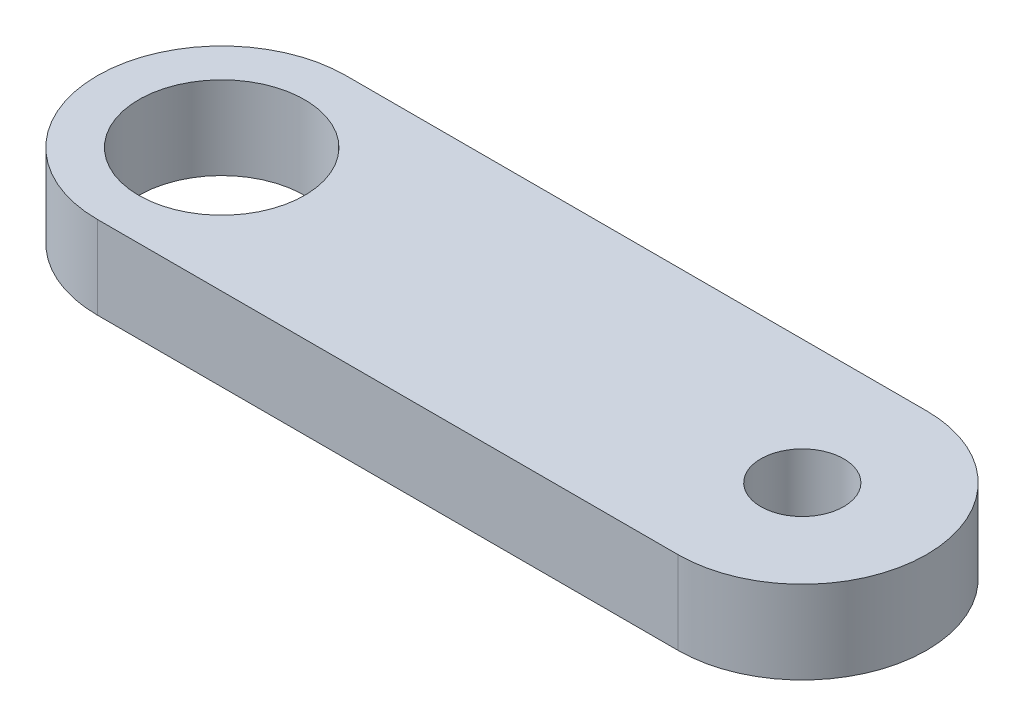
SolidWorks part; units mm, degrees
ref_plane "Front Plane" through (0, 0, 0) normal (0, 0, 1) x (1, 0, 0)
ref_plane "Top Plane" through (0, 0, 0) normal (0, 1, 0) x (1, 0, 0)
ref_plane "Right Plane" through (0, 0, 0) normal (1, 0, 0) x (0, 0, -1)
sketch "Sketch1" plane through (0, 0, 0) normal (0, 1, 0) x (1, 0, 0)
  line L0 (0, 0) -> (35, 0)
  line L1 (35, 0) -> (35, 15) construction
  line L2 (0, 0) -> (0, 15) construction
  line L3 (0, 15) -> (35, 15)
  arc A0 (0, 15) -> (0, 0) centre (0, 7.5) ccw
  arc A1 (35, 0) -> (35, 15) centre (35, 7.5) ccw
  circle A2 centre (35, 7.5) radius 2.5
  circle A3 centre (0, 7.5) radius 5
  dimension "D3" = 10
  dimension "D4" = 5
  dimension "D1" = 35
  dimension "D2" = 15
extrude "Boss-Extrude1" add sketch "Sketch1" along normal blind 5
